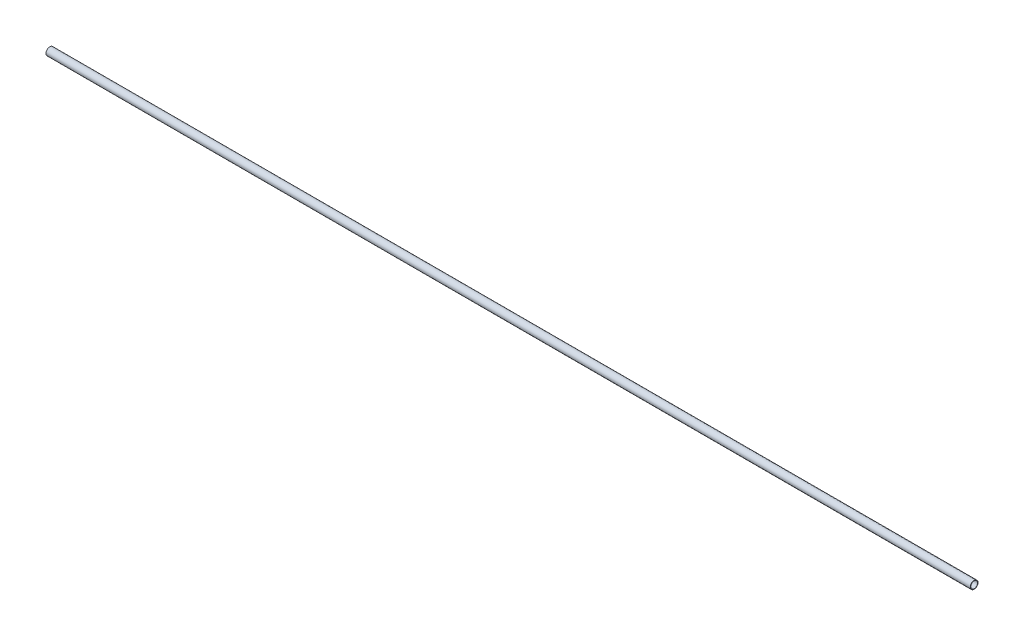
SolidWorks part; units mm, degrees
ref_plane "Front" through (0, 0, 0) normal (0, 0, 1) x (1, 0, 0)
ref_plane "Top" through (0, 0, 0) normal (0, 1, 0) x (1, 0, 0)
ref_plane "Right" through (0, 0, 0) normal (1, 0, 0) x (0, 0, -1)
sketch "Sketch1" plane through (0, 0, 0) normal (1, 0, 0) x (0, 0, -1)
  circle A0 centre (0, 0) radius 6.35
  circle A1 centre (0, 0) radius 5.6388
  point P4 (6.35, 0)
  point P5 (5.6388, 0)
  dimension "OD" = 12.7
  dimension "ID" = 11.2776
  dimension "Wall" = 0.7112
extrude "Extrude1" add sketch "Sketch1" along normal mid plane 1524
